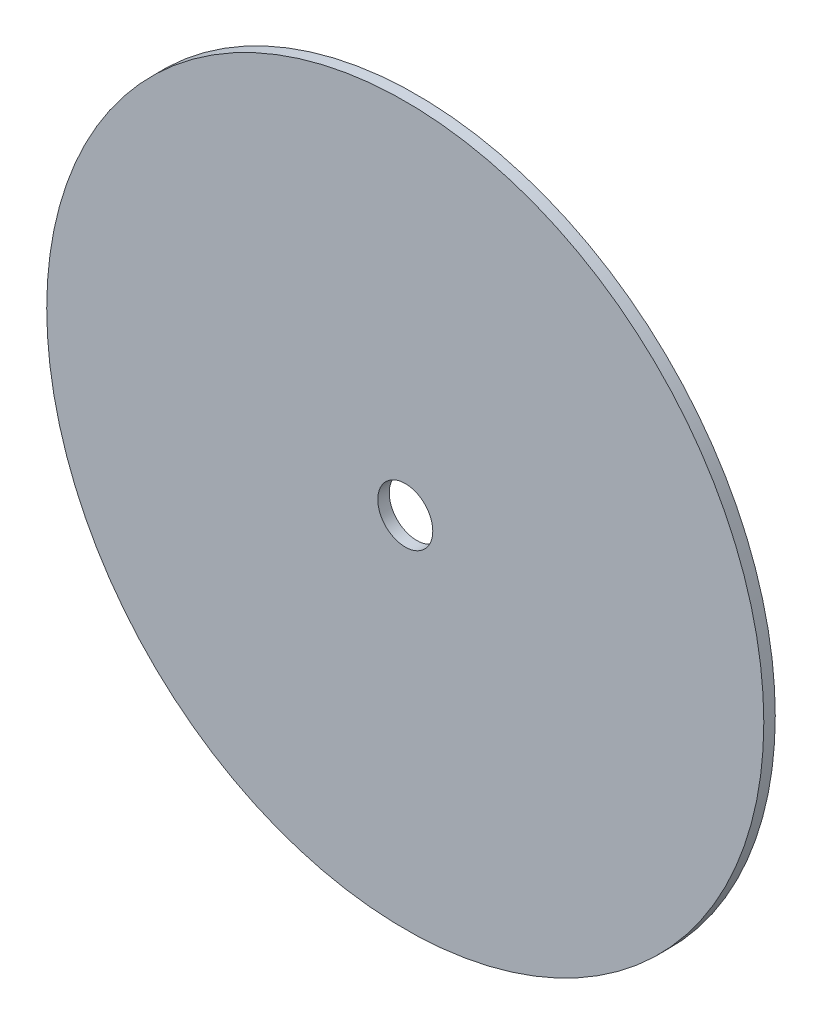
SolidWorks part; units mm, degrees
material "Acrylic (Medium-high impact)"
ref_plane "Front Plane" through (0, 0, 0) normal (0, 0, 1) x (1, 0, 0)
ref_plane "Top Plane" through (0, 0, 0) normal (0, 1, 0) x (1, 0, 0)
ref_plane "Right Plane" through (0, 0, 0) normal (1, 0, 0) x (0, 0, -1)
sketch "Sketch1" plane through (0, 0, 0) normal (0, 0, 1) x (1, 0, 0)
  circle A0 centre (0, 0) radius 3.81
  circle A1 centre (0, 0) radius 49.657
  dimension "D1" = 99.314
  dimension "D2" = 7.62
extrude "Boss-Extrude1" add sketch "Sketch1" along normal blind 1.5875
